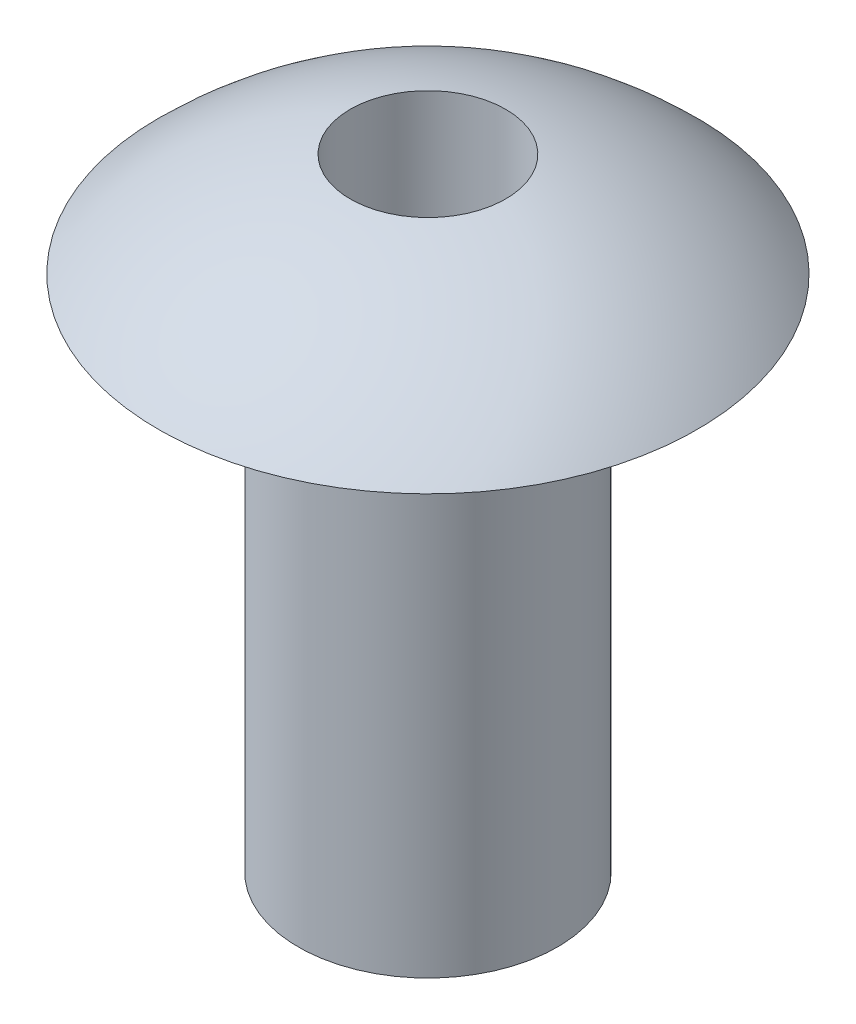
SolidWorks part; units mm, degrees
material "5454-O"
ref_plane "前视基准面" through (0, 0, 0) normal (0, 0, 1) x (1, 0, 0)
ref_plane "上视基准面" through (0, 0, 0) normal (0, 1, 0) x (1, 0, 0)
ref_plane "右视基准面" through (0, 0, 0) normal (1, 0, 0) x (0, 0, -1)
sketch "草图1" plane through (0, 0, 0) normal (0, 0, 1) x (1, 0, 0)
  line L3 (0, -1000) -> (0, 49000) construction
  line L4 (0, -2.8815) -> (-1.5, -2.8815)
  line L6 (-1.5, -2.8815) -> (-1.5, 3.1185)
  line L11 (-1.5, 3.1185) -> (-3.12, 3.1185)
  line L12 (-0.9, 4.3185) -> (-0.9, 1.9185)
  line L13 (-0.9, 1.9185) -> (0, 1.9185)
  line L14 (-1.5, 3.1185) -> (-0.9, 3.1185) construction
  line L15 (0, -2.8815) -> (0, 1.9185)
  arc A2 (-3.12, 3.1185) -> (-0.9, 4.3185) centre (0, 0) cw
  dimension "l" = 6
  dimension "dl" = 1.8
  dimension "dk" = 6.24
  dimension "d" = 3
  dimension "K" = 1.2
revolve "旋转1" add sketch "草图1" angle 360 about L15
fillet "圆角1" [suppressed] radius 0.1
other "冻结***"
